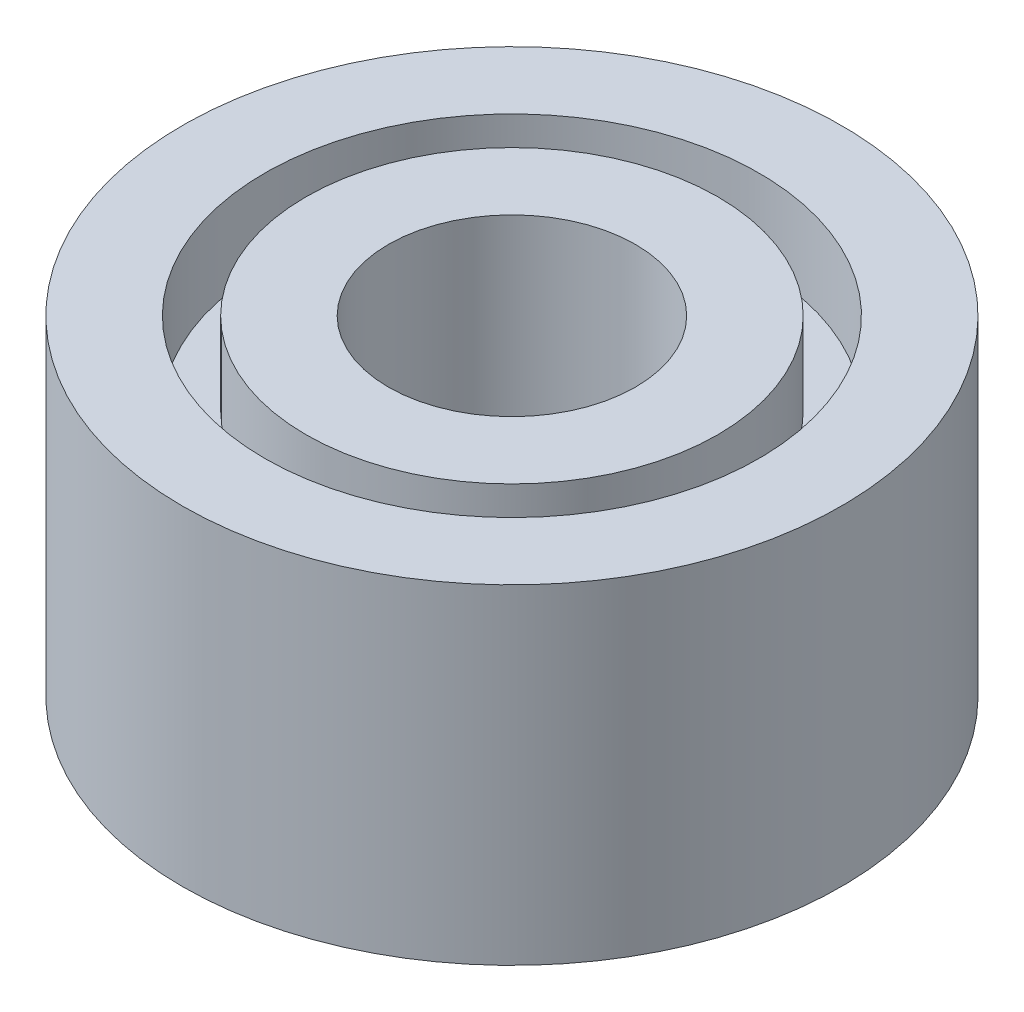
SolidWorks part; units mm, degrees
ref_plane "前视基准面" through (0, 0, 0) normal (0, 0, 1) x (1, 0, 0)
ref_plane "上视基准面" through (0, 0, 0) normal (0, 1, 0) x (1, 0, 0)
ref_plane "右视基准面" through (0, 0, 0) normal (1, 0, 0) x (0, 0, -1)
sketch "草图1" plane through (0, 0, 0) normal (0, 1, 0) x (1, 0, 0)
  circle A0 centre (0, 0) radius 1.5
  circle A1 centre (0, 0) radius 4
  dimension "D1" = 3
  dimension "D2" = 8
extrude "凸台-拉伸1" add sketch "草图1" along normal blind 4
sketch "草图2" plane through (0, 4, 0) normal (0, 1, 0) x (1, 0, 0)
  circle A0 centre (0, 0) radius 2.5
  circle A1 centre (0, 0) radius 3
  dimension "D1" = 5
  dimension "D2" = 6
extrude "切除-拉伸2" cut sketch "草图2" against normal blind 1
ref_plane "基准面1" through (0, 2, 0) normal (0, 1, 0) x (1, 0, 0)
mirror "镜向1" about plane through (0, 2, 0) normal (0, 1, 0) of "切除-拉伸2"
